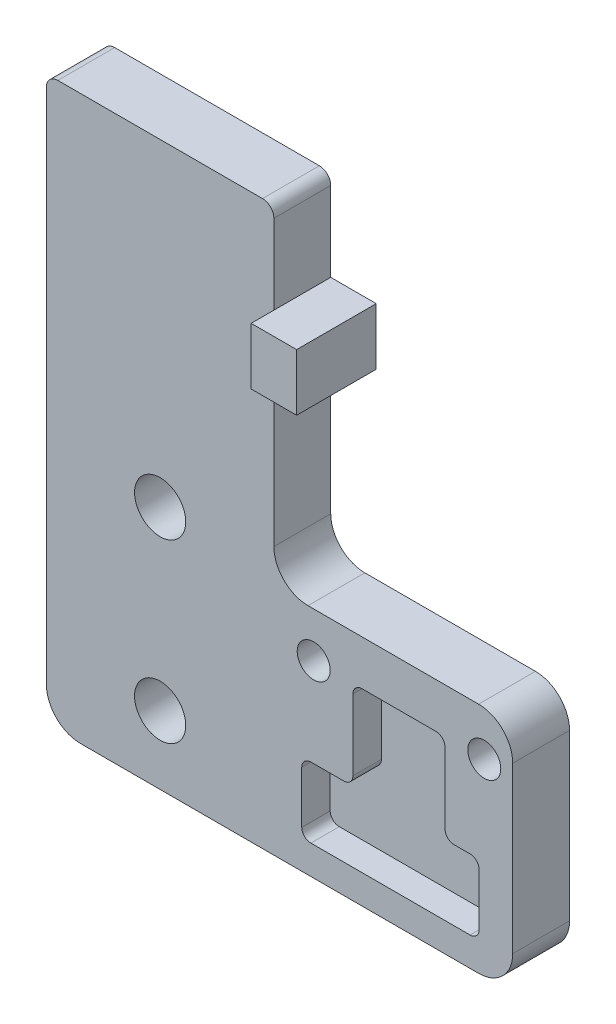
SolidWorks part; units mm, degrees
ref_plane "Ebene vorne" through (0, 0, 0) normal (0, 0, 1) x (1, 0, 0)
ref_plane "Ebene oben" through (0, 0, 0) normal (0, 1, 0) x (1, 0, 0)
ref_plane "Ebene rechts" through (0, 0, 0) normal (1, 0, 0) x (0, 0, -1)
ref_plane "Plane1" through (0, 0, 5) normal (0, 0, 1) x (1, 0, 0)
sketch "Sketch1" plane through (0, 0, 5) normal (0, 0, 1) x (1, 0, 0)
  line L0 (20.5, -10.5) -> (20.5, 39)
  line L1 (20.5, 39) -> (-20.5, 39)
  line L2 (-20.5, 39) -> (-20.5, -10.5)
  line L3 (-20.5, -10.5) -> (20.5, -10.5)
extrude "Boss-Extrude1" add sketch "Sketch1" against normal blind 5
sketch "Sketch2" plane through (0, 0, 5) normal (0, 0, 1) x (1, 0, 0)
  line L0 (-0.5, 39) -> (-0.5, 10)
  line L1 (-0.5, 10) -> (20.5, 10)
  line L2 (20.5, 10) -> (20.5, 39)
  line L3 (20.5, 39) -> (-0.5, 39)
extrude "Cut-Extrude1" cut sketch "Sketch2" against normal through all
sketch "Sketch3" plane through (-0.5, 0, 0) normal (1, 0, 0) x (0, 0, -1)
  line L0 (0, 39) -> (0, 26)
  line L1 (0, 26) -> (-5, 26)
  line L2 (-5, 26) -> (-5, 39)
  line L3 (-5, 39) -> (0, 39)
extrude "Boss-Extrude2" add sketch "Sketch3" along normal blind 4
sketch "Sketch4" plane through (0, 0, 0) normal (0, 0, -1) x (-1, 0, 0)
  line L0 (-3.5, 31) -> (0.5, 31)
  line L1 (0.5, 31) -> (0.5, 39)
  line L2 (0.5, 39) -> (-3.5, 39)
  line L3 (-3.5, 39) -> (-3.5, 31)
extrude "Cut-Extrude2" cut sketch "Sketch4" against normal through all
sketch "Sketch5" plane through (0, 0, 5) normal (0, 0, 1) x (1, 0, 0)
  line L0 (3.5, 31) -> (3.5, 26)
  line L1 (3.5, 26) -> (-0.5, 26)
  line L2 (-0.5, 26) -> (-0.5, 31)
  line L3 (-0.5, 31) -> (3.5, 31)
extrude "Boss-Extrude3" add sketch "Sketch5" along normal blind 2
sketch "Sketch6" plane through (0, 0, 5) normal (0, 0, 1) x (1, 0, 0)
  line L0 (17.55, -1.78) -> (14.55, -1.78)
  line L1 (14.55, -1.78) -> (14.55, 6.05)
  line L2 (14.55, 6.05) -> (6.45, 6.05)
  line L3 (6.45, 6.05) -> (6.45, -1.78)
  line L4 (6.45, -1.78) -> (1.95, -1.78)
  line L5 (1.95, -1.78) -> (1.95, -7.9531)
  line L6 (1.95, -7.9531) -> (17.55, -7.9531)
  line L7 (17.55, -7.9531) -> (17.55, -1.78)
extrude "Cut-Extrude3" cut sketch "Sketch6" against normal blind 2.5
hole_wizard "Ø4.5 (4.5) Diameter Hole1" positions "Sketch8" profile "Sketch7" hole size "Ø4.5" standard "ANSI Metric"
sketch "Sketch8" plane through (0, 0, 0) normal (0, 0, -1) x (-1, 0, 0)
  point P0 (10.5, 11)
  point P1 (10.5, -4.5)
sketch "Sketch7" plane through (-10.5, 11, 0) normal (1, 0, 0) x (0, 1, 0)
  line L0 (0, 0) -> (0, 7)
  line L1 (0, 7) -> (2.25, 7)
  line L2 (2.25, 7) -> (2.25, 0)
  line L5 (2.25, 0) -> (0, 0)
  line L11 (0, -6.35) -> (0, 107.95) construction
  dimension "Thru Hole Dia." = 4.5
  dimension "Thru Hole Depth" = 7
hole_wizard "Ø2.9 (2.9) Diameter Hole1" positions "Sketch10" profile "Sketch9" hole size "Ø2.9" standard "ANSI Metric"
sketch "Sketch10" plane through (0, 0, 0) normal (0, 0, -1) x (-1, 0, 0)
  point P0 (-3, 6.05)
  point P1 (-18, 6.05)
sketch "Sketch9" plane through (3, 6.05, 0) normal (1, 0, 0) x (0, 1, 0)
  line L0 (0, 0) -> (0, 7)
  line L1 (0, 7) -> (1.45, 7)
  line L2 (1.45, 7) -> (1.45, 0)
  line L5 (1.45, 0) -> (0, 0)
  line L11 (0, -6.35) -> (0, 107.95) construction
  dimension "Thru Hole Dia." = 2.9
  dimension "Thru Hole Depth" = 7
fillet "Fillet1" radius 0.8 8 edges at (1.95, -7.9531, 3.75) (14.55, -1.78, 3.75) (17.55, -7.9531, 3.75) (17.55, -1.78, 3.75) (6.45, -1.78, 3.75) (1.95, -1.78, 3.75) (14.55, 6.05, 3.75) (6.45, 6.05, 3.75)
fillet "Fillet2" radius 1 2 edges at (-20.5, 39, 2.5) (-0.5, 39, 2.5)
fillet "Fillet3" radius 3 4 edges at (-0.5, 10, 2.5) (-20.5, -10.5, 2.5) (20.5, 10, 2.5) (20.5, -10.5, 2.5)
